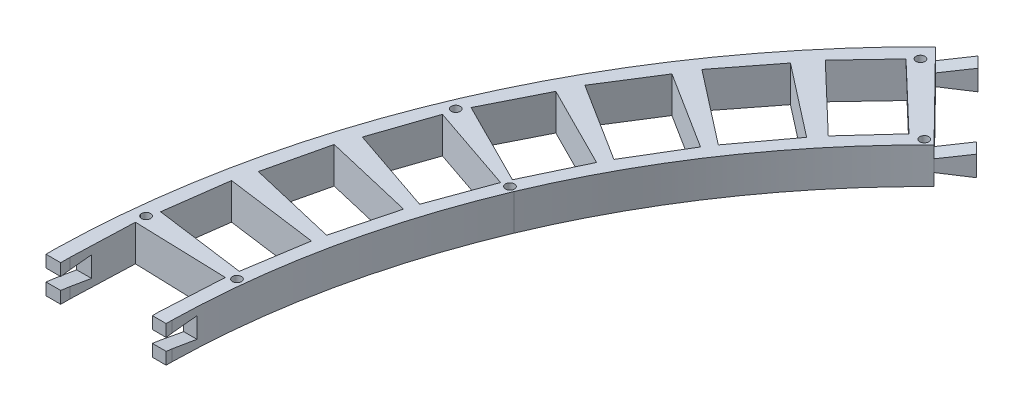
SolidWorks part; units mm, degrees
ref_plane "Front Plane" through (0, 0, 0) normal (0, 0, 1) x (1, 0, 0)
ref_plane "Top Plane" through (0, 0, 0) normal (0, 1, 0) x (1, 0, 0)
ref_plane "Right Plane" through (0, 0, 0) normal (1, 0, 0) x (0, 0, -1)
sketch "Sketch1" plane through (0, 0, 0) normal (0, 1, 0) x (1, 0, 0)
  line L0 (0, -1585.8629) -> (0, 77707.2829) construction
  line L1 (-1585.8629, 0) -> (77707.2829, 0) construction
  line L3 (-206.9013, 210.5443) -> (-178.8649, 182.0143)
  line L38 (0, 0) -> (-235.3327, 98.6832) construction
  line L40 (-289.473, 26.8865) -> (-290.2327, 5.9)
  line L41 (-258.5866, 25.9131) -> (-289.473, 26.8865)
  line L42 (-259.725, 4.9386) -> (-258.5866, 25.9131)
  line L43 (-288.2865, 34.0691) -> (-258.0332, 30.0089)
  line L44 (-285.4916, 54.8823) -> (-288.2865, 34.0691)
  line L45 (-254.767, 50.7589) -> (-285.4916, 54.8823)
  line L46 (-258.0332, 30.0089) -> (-254.767, 50.7589)
  line L47 (-283.6129, 61.9158) -> (-253.8994, 54.9336)
  line L48 (-278.809, 82.359) -> (-283.6129, 61.9158)
  line L49 (-248.631, 75.2676) -> (-278.809, 82.359)
  line L50 (-253.8994, 54.9336) -> (-248.631, 75.2676)
  line L51 (-276.2559, 89.1768) -> (-247.3613, 79.3409)
  line L52 (-269.4887, 109.0566) -> (-276.2559, 89.1768)
  line L53 (-240.1424, 99.0668) -> (-269.4887, 109.0566)
  line L54 (-247.3613, 79.3409) -> (-240.1424, 99.0668)
  line L57 (-290.2327, 5.9) -> (-290.2327, 2.7796)
  line L58 (-295.1278, 6.0543) -> (-295.1278, 2.7796)
  line L59 (-259.725, 4.9386) -> (-259.725, 2.7796)
  line L60 (-255.1446, 4.7942) -> (-255.1446, 2.7796)
  line L62 (-295.1278, 2.7796) -> (-290.2327, 2.7796)
  line L63 (-259.725, 2.7796) -> (-255.1446, 2.7796)
  line L64 (-259.725, 2.7796) -> (-255.1446, 2.7796) construction
  line L79 (-229.9678, 120.8198) -> (-238.9775, 101.8448)
  line L80 (-238.9775, 101.8448) -> (-266.6718, 115.7742)
  line L81 (-266.6718, 115.7742) -> (-257.2357, 134.5348)
  line L82 (-257.2357, 134.5348) -> (-229.9678, 120.8198)
  line L83 (-217.1419, 142.5904) -> (-227.9525, 124.5804)
  line L84 (-227.9525, 124.5804) -> (-254.1624, 141.1345)
  line L85 (-254.1624, 141.1345) -> (-242.9484, 158.8896)
  line L86 (-242.9484, 158.8896) -> (-217.1419, 142.5904)
  line L87 (-202.2618, 163.0088) -> (-214.7723, 146.1353)
  line L88 (-214.7723, 146.1353) -> (-239.2485, 165.1595)
  line L89 (-239.2485, 165.1595) -> (-226.3625, 181.7412)
  line L90 (-226.3625, 181.7412) -> (-202.2618, 163.0088)
  line L91 (-185.5661, 181.7875) -> (-199.7283, 166.2743)
  line L92 (-199.7283, 166.2743) -> (-222.0711, 187.6218)
  line L93 (-222.0711, 187.6218) -> (-207.635, 202.8732)
  line L94 (-207.635, 202.8732) -> (-185.5661, 181.7875)
  arc A0 (-259.7741, 0) -> (-259.7272, 4.9386) centre (0, 0) ccw construction
  arc A1 (-295.1278, 6.0543) -> (-206.9013, 210.5443) centre (0, 0) cw
  arc A3 (-259.7741, 0) -> (-259.7272, 4.9386) centre (0, 0) ccw construction
  arc A4 (-259.7741, 0) -> (-259.7272, 4.9386) centre (0, 0) ccw construction
  arc A5 (-259.7741, 0) -> (-259.7272, 4.9386) centre (0, 0) ccw construction
  arc A6 (-259.7741, 0) -> (-259.7272, 4.9386) centre (0, 0) ccw construction
  arc A7 (-259.7741, 0) -> (-259.7272, 4.9386) centre (0, 0) ccw construction
  arc A8 (-259.7741, 0) -> (-259.7272, 4.9386) centre (0, 0) ccw construction
  arc A9 (-259.7741, 0) -> (-259.7272, 4.9386) centre (0, 0) ccw construction
  circle A10 centre (-205.9232, 204.5554) radius 1.5
  arc A12 (-259.7741, 0) -> (-259.7272, 4.9386) centre (0, 0) ccw construction
  arc A13 (-259.7741, 0) -> (-259.7272, 4.9386) centre (0, 0) ccw construction
  arc A14 (-259.7741, 0) -> (-259.7272, 4.9386) centre (0, 0) ccw construction
  arc A15 (-259.7741, 0) -> (-259.7272, 4.9386) centre (0, 0) ccw construction
  arc A16 (-259.7741, 0) -> (-259.7272, 4.9386) centre (0, 0) ccw construction
  arc A17 (-259.7741, 0) -> (-259.7272, 4.9386) centre (0, 0) ccw construction
  arc A18 (-259.7741, 0) -> (-259.7272, 4.9386) centre (0, 0) ccw construction
  circle A19 centre (-182.1235, 182.0488) radius 1.5
  arc A20 (-235.3327, 98.6832) -> (-178.8649, 182.0143) centre (-0.0003, 0.0121) cw
  arc A21 (-235.3327, 98.6832) -> (-255.1446, 4.7942) centre (-0.0088, -0.0083) ccw
  circle A22 centre (-289.473, 30.4135) radius 1.5
  circle A23 centre (-256.1896, 27.3906) radius 1.5
  circle A24 centre (-237.4451, 99.4921) radius 1.5
  circle A25 centre (-268.8338, 112.8413) radius 1.5
  dimension "D14" = 3
  dimension "D3" = 3
  dimension "D6" = 3
  dimension "D7" = 3
  dimension "D8" = 3
  dimension "D9" = 3
  dimension "D4" = 257.5
  dimension "D5" = 2.3
  dimension "D10" = 5.58
  dimension "D15" = 3.5
  dimension "D21" = 2.4
  dimension "D22" = 5.9
  dimension "D24" = 22.75
  dimension "D11" = 8
  dimension "D18" = 8
extrude "Boss-Extrude1" add sketch "Sketch1" along normal blind 12
sketch "Sketch5" plane through (0, 0, 0) normal (0, -1, 0) x (1, 0, 0)
  line L0 (-206.9013, -210.5443) -> (-178.8649, -182.0143)
  line L1 (-197.2177, -161.9476) -> (-227.6389, -187.9298)
  arc A0 (-178.8649, -182.0143) -> (-197.2177, -161.9476) centre (0, 0) cw
  arc A1 (-206.9013, -210.5443) -> (-227.6389, -187.9298) centre (0, 0) cw
  dimension "D1" = 5
extrude "Cut-Extrude4" [suppressed] cut sketch "Sketch5" against normal blind 6
sketch "Sketch6" plane through (2.2417, 0, -2.3462) normal (-0.6908, 0, 0.723) x (0.723, 0, 0.6908)
  line L0 (-259.7517, 12) -> (-290.2745, 12) construction
  line L1 (-290.5131, 12) -> (-259.5131, 12)
  line L2 (-290.5131, 12) -> (-290.5131, 11)
  line L3 (-290.5131, 11) -> (-259.5131, 11)
  line L4 (-259.5131, 12) -> (-259.5131, 11)
  line L5 (-290.5131, 12) -> (-259.5131, 11) construction
  line L6 (-290.5131, 11) -> (-259.5131, 12) construction
  point P0 (-275.0131, 11.5)
  point P7 (-275.0131, 12)
  dimension "D1" = 1
  dimension "D2" = 31
  dimension "D3" = 0.5
extrude "Boss-Extrude2" add sketch "Sketch6" along normal blind 1
sketch "Sketch7" plane through (-12.2655, 0, 12.8374) normal (0.6908, 0, -0.723) x (-0.723, 0, -0.6908)
  line L0 (290.1762, 12) -> (259.2745, 12) construction
  line L1 (259.2254, 12) -> (290.2254, 12)
  line L2 (259.2254, 12) -> (259.2254, 11)
  line L3 (259.2254, 11) -> (290.2254, 11)
  line L4 (290.2254, 12) -> (290.2254, 11)
  line L5 (259.2254, 12) -> (290.2254, 11) construction
  line L6 (259.2254, 11) -> (290.2254, 12) construction
  point P0 (274.7254, 11.5)
  point P7 (274.7254, 12)
  dimension "D1" = 31
  dimension "D2" = 1
  dimension "D3" = 0.5
extrude "Boss-Extrude3" add sketch "Sketch7" along normal blind 1
sketch "Sketch8" plane through (-12.2655, 0, 12.8374) normal (0.6908, 0, -0.723) x (-0.723, 0, -0.6908)
  line L0 (290.1762, 0) -> (259.2745, 0) construction
  line L1 (260.7254, 1) -> (288.7254, 1)
  line L2 (260.7254, 1) -> (260.7254, 0)
  line L3 (260.7254, 0) -> (288.7254, 0)
  line L4 (288.7254, 1) -> (288.7254, 0)
  line L5 (260.7254, 1) -> (288.7254, 0) construction
  line L6 (260.7254, 0) -> (288.7254, 1) construction
  point P0 (274.7254, 0.5)
  dimension "D1" = 0.5
  dimension "D2" = 28
  dimension "D3" = 1
  dimension "D4" = 0.5
extrude "Boss-Extrude4" add sketch "Sketch8" along normal blind 0.75
sketch "Sketch9" plane through (2.2417, 0, -2.3462) normal (-0.6908, 0, 0.723) x (0.723, 0, 0.6908)
  line L0 (-259.7517, 0) -> (-290.2745, 0) construction
  line L1 (-288.8605, 0) -> (-260.8605, 0)
  line L2 (-288.8605, 0) -> (-288.8605, 1)
  line L3 (-288.8605, 1) -> (-260.8605, 1)
  line L4 (-260.8605, 0) -> (-260.8605, 1)
  line L5 (-288.8605, 0) -> (-260.8605, 1) construction
  line L6 (-288.8605, 1) -> (-260.8605, 0) construction
  point P0 (-274.8605, 0.5)
  point P5 (-274.8605, 0)
  dimension "D1" = 1
  dimension "D2" = 0.5
  dimension "D3" = 28
extrude "Boss-Extrude5" add sketch "Sketch9" along normal blind 0.75
sketch "Sketch10" plane through (-295.1278, 0, 0) normal (-1, 0, 0) x (0, 0, 1)
  line L0 (-2.7796, 12) -> (-2.7796, 8)
  line L1 (-2.7796, 12) -> (-2.7796, 0) construction
  line L5 (-2.7796, 4) -> (-2.7796, 0)
  line L6 (-2.7796, 12) -> (4.5756, 12)
  line L7 (4.5756, 12) -> (4.5756, 0)
  line L8 (4.5756, 0) -> (-2.7796, 0)
  line L9 (-2.7796, 8) -> (-12.7813, 9.4056)
  line L10 (-12.7796, 6) -> (-0.5368, 6) construction
  line L11 (-2.7796, 4) -> (-12.7813, 2.5944)
  line L12 (-12.7813, 2.5944) -> (-12.7813, 9.4056)
  dimension "D1" = 4
  dimension "D3" = 4
  dimension "D5" = 8
  dimension "D6" = 10.1
extrude "Cut-Extrude5" cut sketch "Sketch10" against normal blind 41 contours L8 L5 L11 L12 L9 L0 L6 L7
ref_plane "Plane1" through (7.1325, 0, -7.0091) normal (0.7133, 0, -0.7009) x (-0.7009, 0, -0.7133)
ref_plane "Plane2" through (-206.9013, 0, -210.5443) normal (-0.7009, 0, -0.7133) x (-0.7133, 0, 0.7009)
sketch "Sketch12" plane through (-206.9013, 0, -210.5443) normal (-0.7009, 0, -0.7133) x (-0.7133, 0, 0.7009)
  line L0 (0, 12) -> (0, 8)
  line L1 (0, 12) -> (0, 0) construction
  line L2 (0, 12) -> (0.9017, 12)
  line L3 (-10, 9.4177) -> (-10, 2.6177)
  line L5 (0, 4.0355) -> (0, 0)
  line L6 (0, 0) -> (0.9017, 0)
  line L7 (0, 0) -> (206.2565, 0) construction
  line L8 (0.9017, 0) -> (0.9017, 12)
  line L9 (206.2565, 12) -> (0, 12) construction
  line L10 (0, 8) -> (-10, 9.4177)
  line L12 (-10, 6.0177) -> (0, 6.0177) construction
  line L13 (0, 4.0355) -> (-10, 2.6177)
  dimension "D1" = 4
  dimension "D2" = 6.8
  dimension "D3" = 4.0355
  dimension "D4" = 10
  dimension "D5" = 10.1
extrude "Boss-Extrude6" add sketch "Sketch12" against normal blind 5
ref_plane "Plane3" through (-192.8831, 0, -196.2793) normal (-0.7009, 0, -0.7133) x (-0.7133, 0, 0.7009)
mirror "Mirror2" about plane through (-192.8831, 0, -196.2793) normal (-0.7009, 0, -0.7133) of "Boss-Extrude6"
